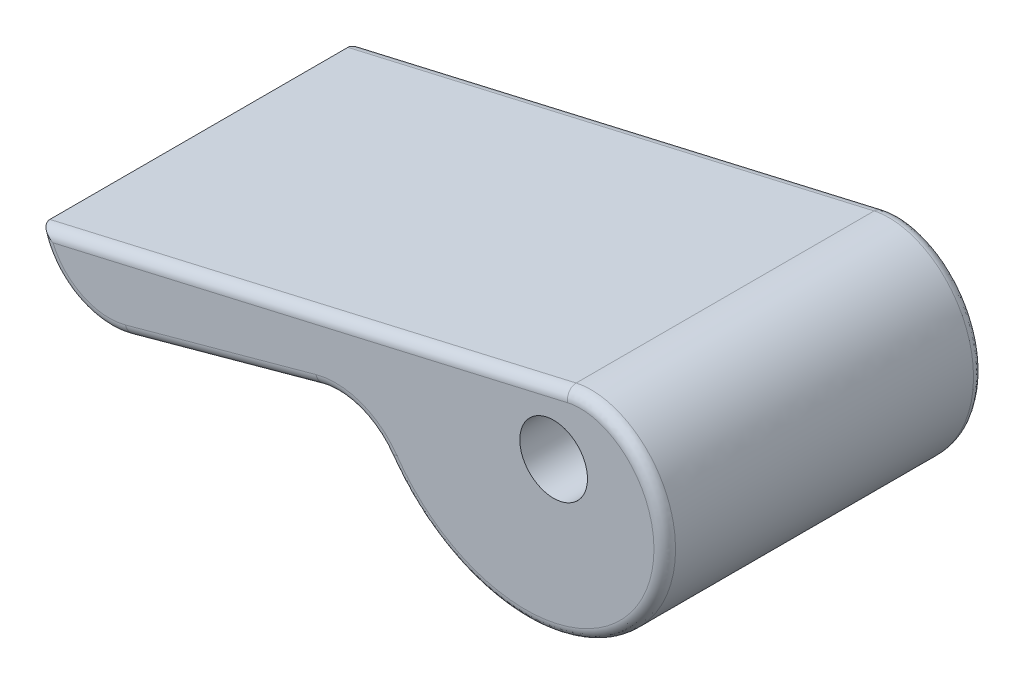
SolidWorks part; units mm, degrees
material "Chrome Stainless Steel"
ref_plane "Front" through (0, 0, 0) normal (0, 0, 1) x (1, 0, 0)
ref_plane "Top" through (0, 0, 0) normal (0, 1, 0) x (1, 0, 0)
ref_plane "Right" through (0, 0, 0) normal (1, 0, 0) x (0, 0, -1)
sketch "Sketch1" plane through (0, 0, 0) normal (0, 0, 1) x (1, 0, 0)
  circle A3 centre (0, 0) radius 4.7625
  dimension "D1" = 9.525
curve "Helix1"
sketch "Sketch2" plane through (0, 0, 0) normal (0, 0, 1) x (1, 0, 0)
  line L0 (0.827, 4.6901) -> (-36.2969, -3.8785)
  line L1 (-16.5639, -3.9449) -> (-30.002, -7.6347)
  arc A0 (-11.7001, -5.7065) -> (-16.5639, -3.9449) centre (-15.3777, -8.265) ccw
  arc A1 (-30.002, -7.6347) -> (-36.2969, -3.8785) centre (-31.3471, -2.7361) cw
  spline S1 degree 3 poles (0.827, 4.6901) (1.2559, 4.7891) (1.7195, 4.8292) (2.6793, 4.7676) (3.1755, 4.6659) (4.1567, 4.3084) (4.6416, 4.0525) (5.5525, 3.3879) (5.9784, 2.9792) (6.7241, 2.0245) (7.0439, 1.4785) (7.5349, 0.2793) (7.7061, -0.374) (7.8666, -1.7454) (7.8558, -2.4634) (7.6314, -3.9121) (7.4177, -4.6425) (6.782, -6.0577) (6.3599, -6.7423) (5.3186, -8.0056) (4.6994, -8.5842) (3.2926, -9.579) (2.5049, -9.9951) (0.8057, -10.6164) (-0.1057, -10.8215) (-1.9941, -10.9852) (-2.9709, -10.9437) (-4.9219, -10.5951) (-5.8958, -10.2879) (-7.7677, -9.408) (-8.6654, -8.8352) (-10.3116, -7.4445) (-11.0599, -6.6266) (-11.7001, -5.7065) knots 0 0 0 0 0.0625 0.0625 0.125 0.125 0.1875 0.1875 0.25 0.25 0.3125 0.3125 0.375 0.375 0.4375 0.4375 0.5 0.5 0.5625 0.5625 0.625 0.625 0.6875 0.6875 0.75 0.75 0.8125 0.8125 0.875 0.875 0.9375 0.9375 1 1 1 1
  spline S2 degree 3 poles (0.827, 4.6901) (1.2559, 4.7891) (1.7195, 4.8292) (2.6793, 4.7676) (3.1755, 4.6659) (4.1567, 4.3084) (4.6416, 4.0525) (5.5525, 3.3879) (5.9784, 2.9792) (6.7241, 2.0245) (7.0439, 1.4785) (7.5349, 0.2793) (7.7061, -0.374) (7.8666, -1.7454) (7.8558, -2.4634) (7.6314, -3.9121) (7.4177, -4.6425) (6.782, -6.0577) (6.3599, -6.7423) (5.3186, -8.0056) (4.6994, -8.5842) (3.2926, -9.579) (2.5049, -9.9951) (0.8057, -10.6164) (-0.1057, -10.8215) (-1.9941, -10.9852) (-2.9709, -10.9437) (-4.9219, -10.5951) (-5.8958, -10.2879) (-7.7677, -9.408) (-8.6654, -8.8352) (-10.3116, -7.4445) (-11.0599, -6.6266) (-11.7001, -5.7065) knots 0 0 0 0 0.0625 0.0625 0.125 0.125 0.1875 0.1875 0.25 0.25 0.3125 0.3125 0.375 0.375 0.4375 0.4375 0.5 0.5 0.5625 0.5625 0.625 0.625 0.6875 0.6875 0.75 0.75 0.8125 0.8125 0.875 0.875 0.9375 0.9375 1 1 1 1
  dimension "D3" = 5.08
  dimension "D2" = 38.1
  dimension "D1" = 0
extrude "Extrude1" add sketch "Sketch2" along normal mid plane 22.5425
sketch "Sketch3" plane through (0, 0, 11.2712) normal (0, 0, 1) x (1, 0, 0)
  circle A0 centre (0, 0) radius 2.3876
  dimension "D1" = 4.7752
extrude "Cut-Extrude1" cut sketch "Sketch3" against normal through all
fillet "Fillet2" radius 0.762 10 edges at (-13.852, -4.0527, -11.2712) (-23.2829, -5.7898, -11.2712) (-13.852, -4.0527, 11.2712) (-23.2829, -5.7898, 11.2712) (-17.735, 0.4058, -11.2712) (-17.735, 0.4058, 11.2712) (-33.9501, -7.0985, -11.2712) (-33.9501, -7.0985, 11.2712)
